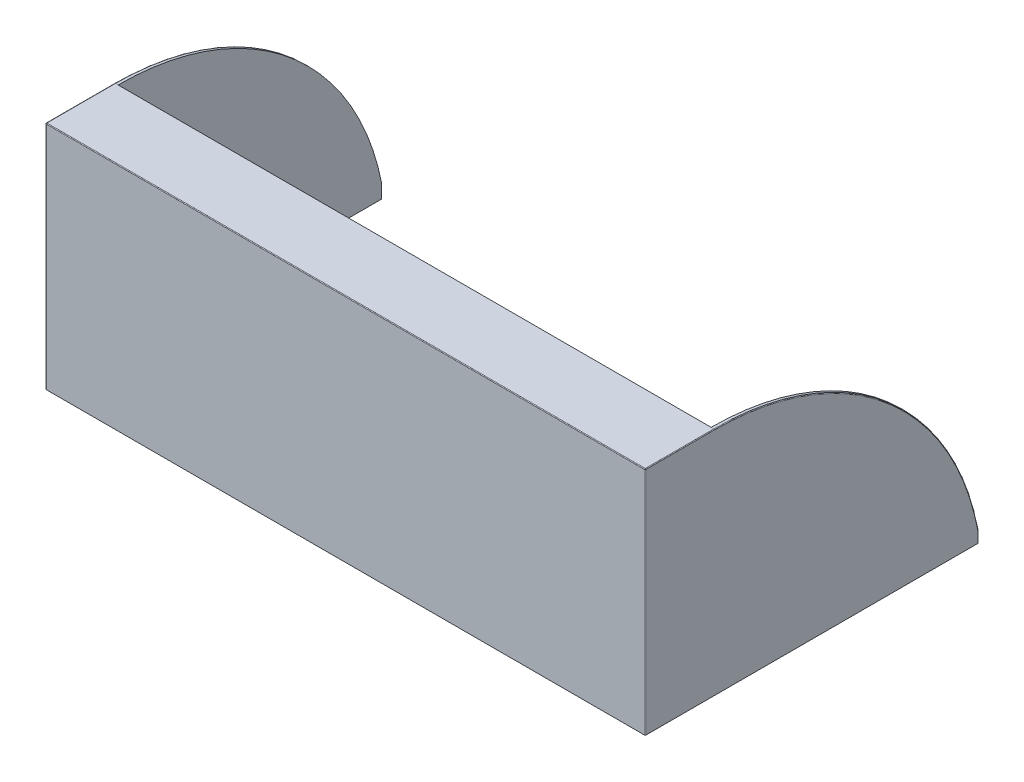
SolidWorks part; units mm, degrees
ref_plane "Front Plane" through (0, 0, 0) normal (0, 0, 1) x (1, 0, 0)
ref_plane "Top Plane" through (0, 0, 0) normal (0, 1, 0) x (1, 0, 0)
ref_plane "Right Plane" through (0, 0, 0) normal (1, 0, 0) x (0, 0, -1)
sketch "Sketch1" plane through (0, 0, 0) normal (0, 1, 0) x (1, 0, 0)
  line L0 (0, 0) -> (0, 88.1849) construction
  line L1 (-90, 0) -> (-90, 20)
  line L2 (-90, 0) -> (90, 0)
  line L3 (0, 0) -> (0, 20)
  line L4 (-90, 20) -> (90, 20)
  line L5 (90, 0) -> (90, 20)
  dimension "D1" = 180
  dimension "D2" = 20
extrude "Boss-Extrude2" add sketch "Sketch1" along normal blind 1 contours L2 L5 L4 L1
sketch "Sketch3" plane through (90, 0, 0) normal (1, 0, 0) x (0, 0, -1)
  line L0 (0, 1) -> (0, -69)
  line L1 (0, -69) -> (100, -69)
  line L2 (100, -69) -> (100, -64.8928)
  line L3 (0, 1) -> (20, 1)
  arc A0 (20, 1) -> (100, -64.8928) centre (20, -80.5101) cw
  point P9 (0, 0)
  dimension "D4" = 20
  dimension "D1" = 100
  dimension "D2" = 4.1072
  dimension "D3" = 70
extrude "Boss-Extrude3" add sketch "Sketch3" along normal blind 1
sketch "Sketch5" plane through (-90, 0, 0) normal (-1, 0, 0) x (0, 0, 1)
  line L0 (0, 1) -> (-20, 1)
  line L1 (0, 1) -> (0, -69)
  line L2 (0, -69) -> (-100, -69)
  line L3 (-100, -69) -> (-100, -64.8928)
  arc A0 (-20, 1) -> (-100, -64.8928) centre (-20, -80.5101) ccw
extrude "Boss-Extrude5" add sketch "Sketch5" along normal blind 1
sketch "Sketch6" plane through (0, 0, 0) normal (0, 0, 1) x (1, 0, 0)
  line L0 (-91, -69) -> (91, -69)
  line L1 (91, 1) -> (-91, 1)
  line L2 (-91, 1) -> (-91, -69)
  line L11 (-90, 0) -> (90, 0)
  line L12 (90, 0) -> (90, -69)
  line L13 (90, -69) -> (91, -69)
  line L14 (91, -69) -> (91, 1)
  line L15 (91, 1) -> (-91, 1)
  line L16 (-91, 1) -> (-91, -69)
  line L17 (-91, -69) -> (-90, -69)
  line L18 (-90, -69) -> (-90, 0)
  line L22 (91, -69) -> (91, 1)
  dimension "D1" = 0
extrude "Boss-Extrude6" add sketch "Sketch6" along normal blind 1
fillet "Fillet2" radius 0.2 7 edges at (-91, -17.594, -71.8215) (91, -17.594, -71.8215) (-91, -34, 1) (91, -34, 1) (-91, 1, -9.5) (0, 1, 1) (91, 1, -9.5)
